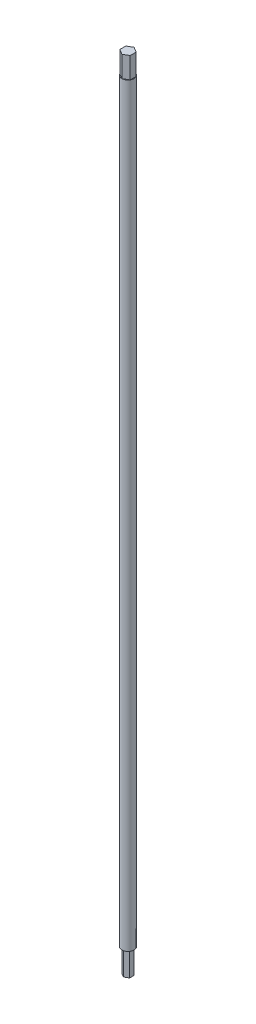
SolidWorks part; units mm, degrees
ref_plane "Piano frontale" through (0, 0, 0) normal (0, 0, 1) x (1, 0, 0)
ref_plane "Piano superiore" through (0, 0, 0) normal (0, 1, 0) x (1, 0, 0)
ref_plane "Piano destro" through (0, 0, 0) normal (1, 0, 0) x (0, 0, -1)
sketch "Schizzo1" plane through (0, 0, 0) normal (0, 1, 0) x (1, 0, 0)
  circle A0 centre (0, 0) radius 2
  dimension "D1" = 4
extrude "Estrusione-Estrusione1" add sketch "Schizzo1" along normal blind 250
sketch "Schizzo2" plane through (0, 0, 0) normal (0, -1, 0) x (1, 0, 0)
  line L1 (0, 1.5) -> (-1.299, 0.75)
  line L2 (-1.299, 0.75) -> (-1.299, -0.75)
  line L3 (-1.299, -0.75) -> (0, -1.5)
  line L4 (0, -1.5) -> (1.299, -0.75)
  line L5 (1.299, -0.75) -> (1.299, 0.75)
  line L6 (1.299, 0.75) -> (0, 1.5)
  circle A0 centre (0, 0) radius 1.299 construction
  dimension "D1" = 1.5
extrude "Estrusione-Estrusione2" add sketch "Schizzo2" along normal blind 8
sketch "Schizzo3" plane through (0, 250, 0) normal (0, 1, 0) x (1, 0, 0)
  line L1 (0, 2) -> (-1.7321, 1)
  line L2 (-1.7321, 1) -> (-1.7321, -1)
  line L3 (-1.7321, -1) -> (0, -2)
  line L4 (0, -2) -> (1.7321, -1)
  line L5 (1.7321, -1) -> (1.7321, 1)
  line L6 (1.7321, 1) -> (0, 2)
  circle A0 centre (0, 0) radius 1.7321 construction
  dimension "D1" = 2
extrude "Estrusione-Estrusione3" add sketch "Schizzo3" along normal blind 7
